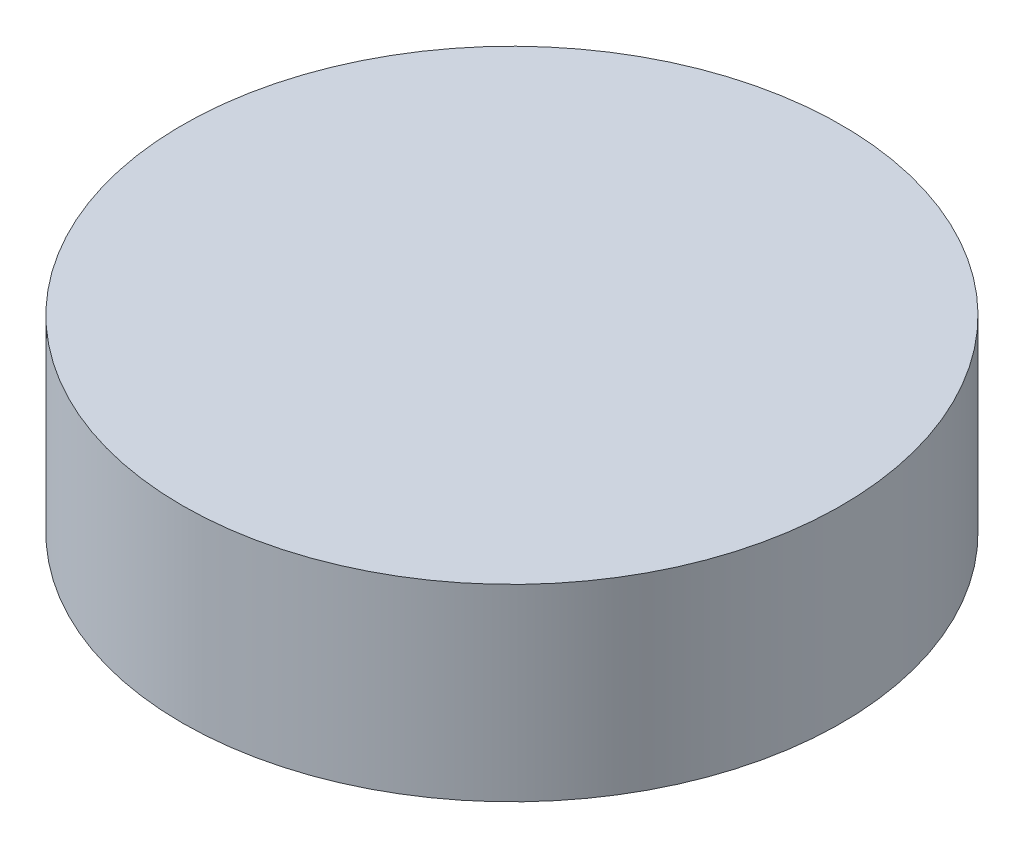
SolidWorks part; units mm, degrees
ref_plane "Спереди" through (0, 0, 0) normal (0, 0, 1) x (1, 0, 0)
ref_plane "Сверху" through (0, 0, 0) normal (0, 1, 0) x (1, 0, 0)
ref_plane "Справа" through (0, 0, 0) normal (1, 0, 0) x (0, 0, -1)
sketch "Sketch1" plane through (0, 0, 0) normal (0, 1, 0) x (1, 0, 0)
  circle A0 centre (0, 0) radius 3.5
  dimension "D3" = 7
extrude "Boss-Extrude1" add sketch "Sketch1" along normal blind 2
